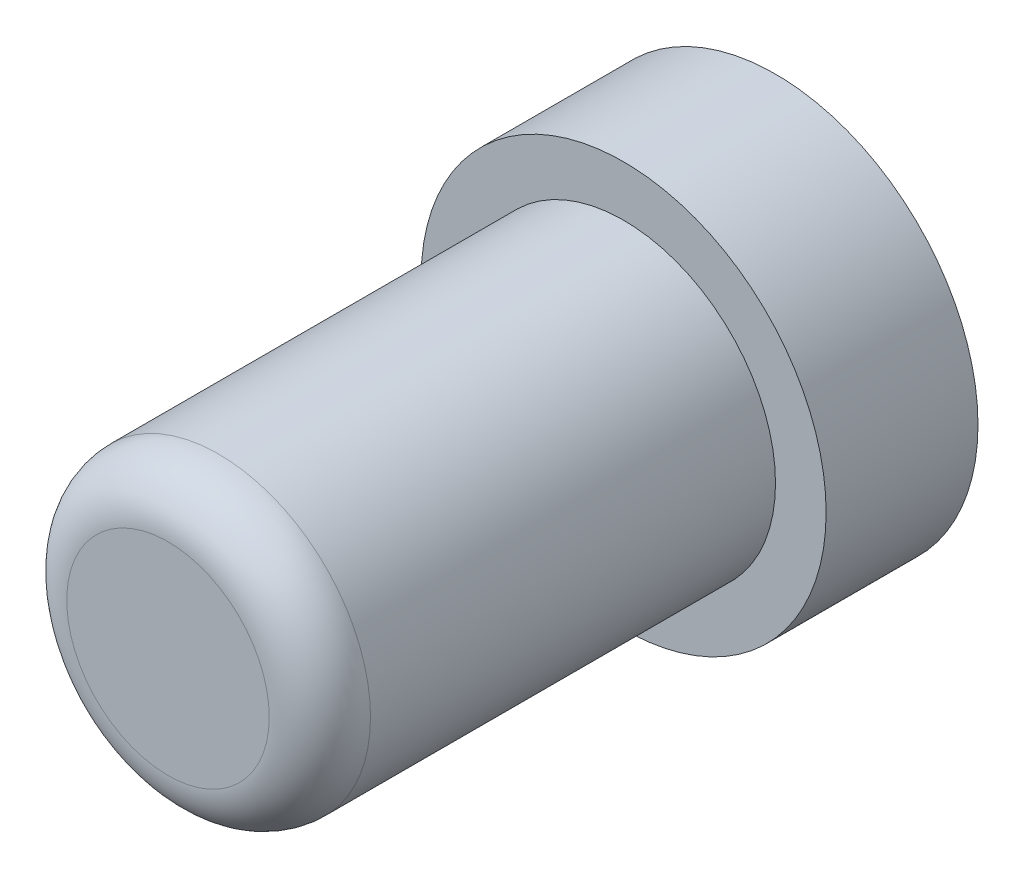
SolidWorks part; units mm, degrees
ref_plane "Спереди" through (0, 0, 0) normal (0, 0, 1) x (1, 0, 0)
ref_plane "Сверху" through (0, 0, 0) normal (0, 1, 0) x (1, 0, 0)
ref_plane "Справа" through (0, 0, 0) normal (1, 0, 0) x (0, 0, -1)
sketch "Sketch1" plane through (0, 0, 0) normal (0, 0, 1) x (1, 0, 0)
  circle A0 centre (0, 0) radius 2
  dimension "D1" = 4
extrude "Boss-Extrude1" add sketch "Sketch1" along normal blind 1.5
sketch "Sketch2" plane through (0, 0, 1.5) normal (0, 0, 1) x (1, 0, 0)
  circle A0 centre (0, 0) radius 1.5
  dimension "D1" = 3
extrude "Boss-Extrude2" add sketch "Sketch2" along normal blind 4.5
fillet "Fillet1" radius 0.5 1 edges at (1.5, 0, 6)
